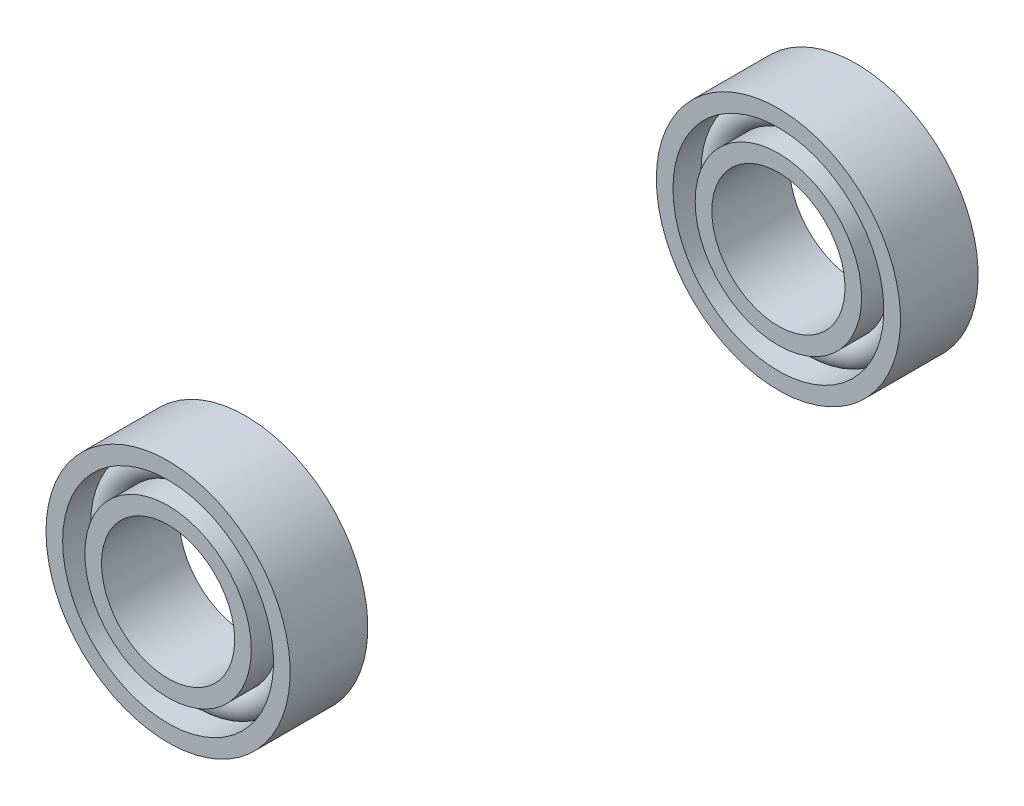
SolidWorks part; units mm, degrees
material "Acero inoxidable al cromo"
ref_plane "Alzado" through (0, 0, 0) normal (0, 0, 1) x (1, 0, 0)
ref_plane "Planta" through (0, 0, 0) normal (0, 1, 0) x (1, 0, 0)
ref_plane "Vista lateral" through (0, 0, 0) normal (1, 0, 0) x (0, 0, -1)
sketch "Sk_Pista_int_1" plane through (0, 0, 0) normal (0, 1, 0) x (1, 0, 0)
  line L0 (178.5, -84.5) -> (180, -84.5)
  line L1 (180, -84.5) -> (180, -91.5)
  line L2 (180, -91.5) -> (178.5, -91.5)
  line L3 (178.5, -91.5) -> (178.5, -84.5)
  line L4 (172.5, -79.5) -> (172.5, -96.5) construction
revolve "Pista_int_1" add sketch "Sk_Pista_int_1" angle 360 about L4
sketch "Sk_Pista_ext_1" plane through (0, 0, 0) normal (0, 1, 0) x (1, 0, 0)
  line L0 (182, -84.5) -> (183.5, -84.5)
  line L1 (183.5, -84.5) -> (183.5, -91.5)
  line L2 (183.5, -91.5) -> (182, -91.5)
  line L3 (182, -91.5) -> (182, -84.5)
  line L4 (172.5, -79.5) -> (172.5, -96.5) construction
revolve "Pista_ext_1" add sketch "Sk_Pista_ext_1" angle 360 about L4
sketch "Sk_Bolas_1" plane through (0, 0, 0) normal (0, 1, 0) x (1, 0, 0)
  line L0 (172.5, -83) -> (172.5, -93) construction
  circle A0 centre (181, -88) radius 1.4
  dimension "DIAM1" = 2.8
revolve "Bolas_1" add sketch "Sk_Bolas_1" angle 360 about L0
sketch "Sk_Pista_int_2" plane through (0, 0, 0) normal (0, 1, 0) x (1, 0, 0)
  line L0 (178.5, -139.5) -> (180, -139.5)
  line L1 (180, -139.5) -> (180, -146.5)
  line L2 (180, -146.5) -> (178.5, -146.5)
  line L3 (178.5, -146.5) -> (178.5, -139.5)
  line L4 (172.5, -134.5) -> (172.5, -151.5) construction
revolve "Pista_int_2" add sketch "Sk_Pista_int_2" angle 360 about L4
sketch "Sk_Pista_ext_2" plane through (0, 0, 0) normal (0, 1, 0) x (1, 0, 0)
  line L0 (182, -139.5) -> (183.5, -139.5)
  line L1 (183.5, -139.5) -> (183.5, -146.5)
  line L2 (183.5, -146.5) -> (182, -146.5)
  line L3 (182, -146.5) -> (182, -139.5)
  line L4 (172.5, -134.5) -> (172.5, -151.5) construction
revolve "Pista_ext_2" add sketch "Sk_Pista_ext_2" angle 360 about L4
sketch "Sk_Bolas_2" plane through (0, 0, 0) normal (0, 1, 0) x (1, 0, 0)
  line L0 (172.5, -138) -> (172.5, -148) construction
  circle A0 centre (181, -143) radius 1.4
  dimension "DIAM2" = 2.8
revolve "Bolas_2" add sketch "Sk_Bolas_2" angle 360 about L0
